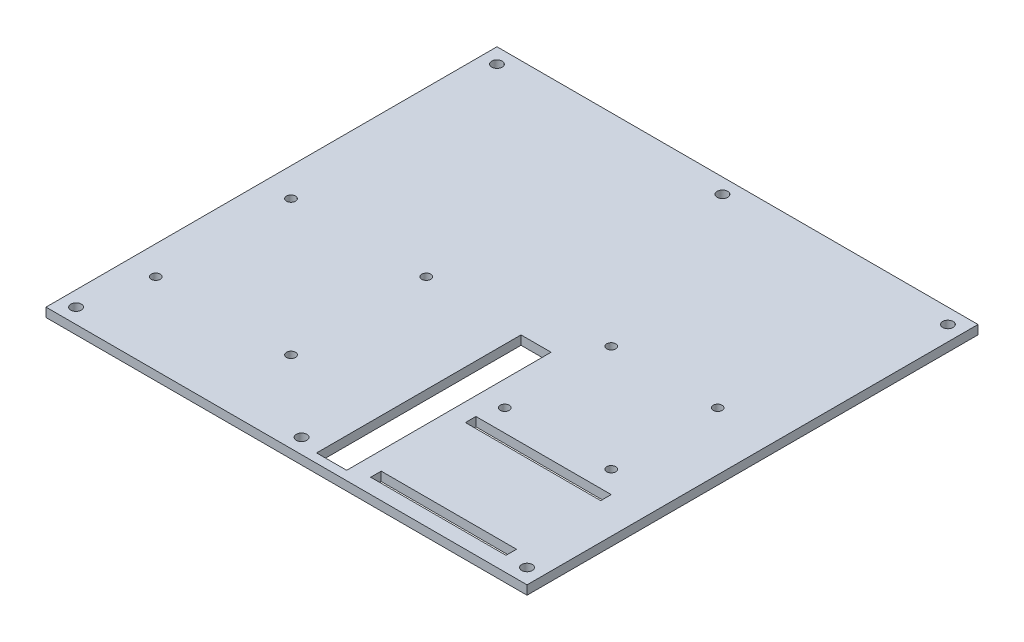
SolidWorks part; units mm, degrees
material "Manual Density from Real Component Mass Base elettronica"
ref_plane "Piano frontale" through (0, 0, 0) normal (0, 0, 1) x (1, 0, 0)
ref_plane "Piano superiore" through (0, 0, 0) normal (0, 1, 0) x (1, 0, 0)
ref_plane "Piano destro" through (0, 0, 0) normal (1, 0, 0) x (0, 0, -1)
sketch "Schizzo1" plane through (0, 0, 0) normal (0, 1, 0) x (1, 0, 0)
  line L1 (80, -75) -> (-80, -75)
  line L2 (80, -75) -> (80, 75)
  line L3 (80, 75) -> (-80, 75)
  line L4 (-80, -75) -> (-80, 75)
  line L5 (80, -75) -> (-80, 75) construction
  line L6 (80, 75) -> (-80, -75) construction
  point P0 (0, 0)
  dimension "D1" = 150
  dimension "D2" = 160
extrude "Base" add sketch "Schizzo1" along normal blind 3
sketch "Schizzo2" plane through (0, 3, 0) normal (0, 1, 0) x (1, 0, 0)
  line L0 (0, -75) -> (0, -72) construction
  line L1 (-80, -75) -> (80, -75) construction
  line L2 (0, -72) -> (-48, -72) construction
  line L3 (-48, -72) -> (-53, -72) construction
  line L4 (-53, -72) -> (-63, -72)
  line L5 (-53, -72) -> (-53, -4)
  line L6 (-53, -4) -> (-63, -4)
  line L7 (-63, -72) -> (-63, -4)
  line L8 (-53, -72) -> (-63, -4) construction
  line L9 (-53, -4) -> (-63, -72) construction
  point P4 (-58, -38)
  dimension "D1" = 3
  dimension "D2" = 48
  dimension "D3" = 10
  dimension "D4" = 68
  dimension "D5" = 5
extrude "TaglioPMSinistra" cut sketch "Schizzo2" against normal through all
sketch "Schizzo5" plane through (0, 3, 0) normal (0, 1, 0) x (1, 0, 0)
  line L0 (-53, -72) -> (-23, -72) construction
  dimension "D1" = 30
ref_plane "PianoMedioPM" through (-23, 0, 0) normal (1, 0, 0) x (0, 0, -1)
mirror "TaglioPMDestra" about plane through (-23, 0, 0) normal (1, 0, 0) of "TaglioPMSinistra"
sketch "Schizzo6" plane through (0, 3, 0) normal (0, 1, 0) x (1, 0, 0)
  line L0 (80, -75) -> (80, 75) construction
  line L1 (68, -70) -> (23, -70)
  line L2 (68, -70) -> (68, -66.5)
  line L3 (68, -66.5) -> (23, -66.5)
  line L4 (23, -70) -> (23, -66.5)
  line L5 (68, -70) -> (23, -66.5) construction
  line L6 (68, -66.5) -> (23, -70) construction
  line L7 (-80, -75) -> (80, -75) construction
  point P0 (45.5, -68.25)
  dimension "D1" = 12
  dimension "D2" = 3.5
  dimension "D3" = 45
  dimension "D4" = 5
extrude "ForoBECBasso" cut sketch "Schizzo6" against normal through all
sketch "Schizzo7" plane through (0, 0, 0) normal (0, 1, 0) x (1, 0, 0)
  line L0 (80, -75) -> (80, -52.5) construction
  dimension "D1" = 22.5
ref_plane "PianoMedioBEC" through (0, 0, 52.5) normal (0, 0, 1) x (1, 0, 0)
mirror "ForoBECAlto" about plane through (0, 0, 52.5) normal (0, 0, 1) of "ForoBECBasso"
sketch "Schizzo8" plane through (0, 3, 0) normal (0, 1, 0) x (1, 0, 0)
  line L0 (-53, -72) -> (-53, -4) construction
  line L3 (-53, -4) -> (7, -4) construction
  circle A0 centre (-70.5, -3) radius 1.5
  circle A1 centre (-70.5, -48) radius 1.5
  circle A2 centre (-25.5, -48) radius 1.5
  circle A3 centre (-25.5, -3) radius 1.5
  dimension "D1" = 3
  dimension "D2" = 3
  dimension "D3" = 17.5
  dimension "D4" = 45
  dimension "D5" = 24
  dimension "D6" = 45
  dimension "D7" = 45
  dimension "D8" = 45
extrude "ForiVitiPM" cut sketch "Schizzo8" against normal through all
sketch "Schizzo9" plane through (0, 3, 0) normal (0, 1, 0) x (1, 0, 0)
  line L0 (23, -35) -> (68, -35) construction
  line L1 (80, -75) -> (80, 75) construction
  circle A0 centre (60.7, -27.7) radius 1.5
  circle A1 centre (25.3, -27.7) radius 1.5
  circle A2 centre (25.3, 7.7) radius 1.5
  circle A3 centre (60.7, 7.7) radius 1.5
  dimension "D1" = 3
  dimension "D2" = 35.4
  dimension "D3" = 35.4
  dimension "D4" = 7.3
  dimension "D5" = 19.3
extrude "ForiVitiCompanion" cut sketch "Schizzo9" against normal through all
sketch "Schizzo12" plane through (0, 3, 0) normal (0, 1, 0) x (1, 0, 0)
  line L0 (80, 75) -> (-80, 75) construction
  line L1 (-80, 75) -> (-80, -75) construction
  line L2 (0, -1.65) -> (0, 1.65) construction
  line L3 (80, -75) -> (80, 75) construction
  line L4 (-80, -75) -> (80, -75) construction
  circle A0 centre (-75, 70) radius 1.75
  circle A1 centre (75, 70) radius 1.75
  circle A2 centre (0, 70) radius 1.75
  circle A3 centre (-75, -70) radius 1.75
  circle A4 centre (0, -70) radius 1.75
  circle A5 centre (75, -70) radius 1.75
  circle A6 centre (-75, 70) radius 5 construction
  circle A7 centre (75, -70) radius 5 construction
  dimension "D1" = 3.5
  dimension "D2" = 10
  dimension "D3" = 10
extrude "ForiCollegamentoFusoliera" cut sketch "Schizzo12" against normal through all
sketch "Schizzo13" plane through (0, 3, 0) normal (0, 1, 0) x (1, 0, 0)
  line L1 (-63, -4) -> (-53, -4)
  line L2 (-63, -4) -> (-63, -72)
  line L3 (-63, -72) -> (-53, -72)
  line L4 (-53, -4) -> (-53, -72)
extrude "ChiusuraTaglioSinistroPM" add sketch "Schizzo13" against normal through all
